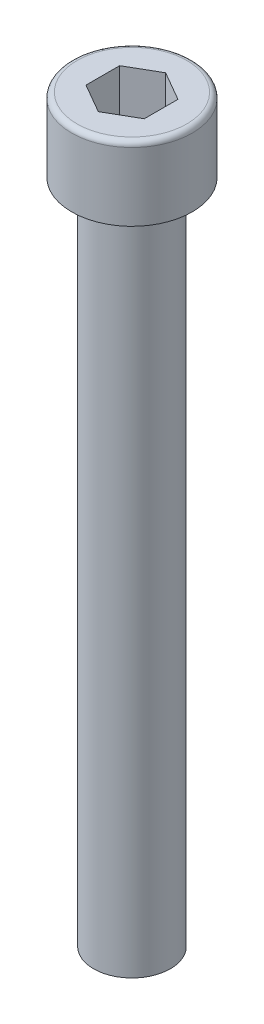
SolidWorks part; units mm, degrees
ref_plane "Front Plane" through (0, 0, 0) normal (0, 0, 1) x (1, 0, 0)
ref_plane "Top Plane" through (0, 0, 0) normal (0, 1, 0) x (1, 0, 0)
ref_plane "Right Plane" through (0, 0, 0) normal (1, 0, 0) x (0, 0, -1)
sketch "Sketch1" plane through (0, 0, 0) normal (0, 1, 0) x (1, 0, 0)
  circle A0 centre (0, 0) radius 1.8288
  dimension "D1" = 3.6576
extrude "Boss-Extrude1" add sketch "Sketch1" against normal blind 31.75
sketch "Sketch2" plane through (0, 0, 0) normal (0, 1, 0) x (1, 0, 0)
  circle A0 centre (0, 0) radius 2.8702
  dimension "D1" = 5.7404
extrude "Boss-Extrude2" add sketch "Sketch2" along normal blind 3.5052
fillet "Fillet1" radius 0.254 1 edges at (0, 3.5052, 2.8702)
sketch "Sketch3" plane through (0, 3.5052, 0) normal (0, 1, 0) x (1, 0, 0)
  line L1 (0, 1.604) -> (-1.3891, 0.802)
  line L2 (-1.3891, 0.802) -> (-1.3891, -0.802)
  line L3 (-1.3891, -0.802) -> (0, -1.604)
  line L4 (0, -1.604) -> (1.3891, -0.802)
  line L5 (1.3891, -0.802) -> (1.3891, 0.802)
  line L6 (1.3891, 0.802) -> (0, 1.604)
  circle A0 centre (0, 0) radius 1.3891 construction
  dimension "D1" = 2.7781
extrude "Cut-Extrude1" cut sketch "Sketch3" against normal blind 2.54
